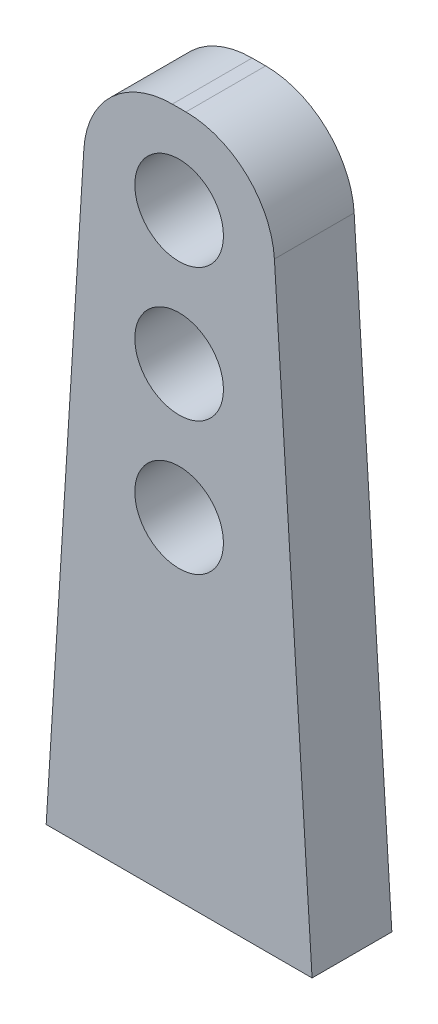
SolidWorks part; units mm, degrees
ref_plane "Front Plane" through (0, 0, 0) normal (0, 0, 1) x (1, 0, 0)
ref_plane "Top Plane" through (0, 0, 0) normal (0, 1, 0) x (1, 0, 0)
ref_plane "Right Plane" through (0, 0, 0) normal (1, 0, 0) x (0, 0, -1)
sketch "Sketch1" plane through (0, 0, 0) normal (0, 0, 1) x (1, 0, 0)
  line L0 (1.5699, 7.7018) -> (1.4162, 7.7018)
  line L1 (0.4182, 6.7641) -> (-0.0071, -0.0482)
  line L2 (-0.0071, -0.0482) -> (2.9929, -0.0482)
  line L3 (2.9929, -0.0482) -> (2.5679, 6.7641)
  arc A0 (2.5679, 6.7641) -> (1.5699, 7.7018) centre (1.5699, 6.7018) ccw
  arc A1 (1.4162, 7.7018) -> (0.4182, 6.7641) centre (1.4162, 6.7018) ccw
  circle A2 centre (1.4929, 3.7018) radius 0.5
  circle A3 centre (1.4929, 5.2018) radius 0.5
  circle A4 centre (1.4929, 6.7018) radius 0.5
  point P14 (0, 0)
extrude "Boss-Extrude1" add sketch "Sketch1" along normal blind 0.8999 contours A2 | A3 | A4 | L3 A0 L0 A1 L1 L2
